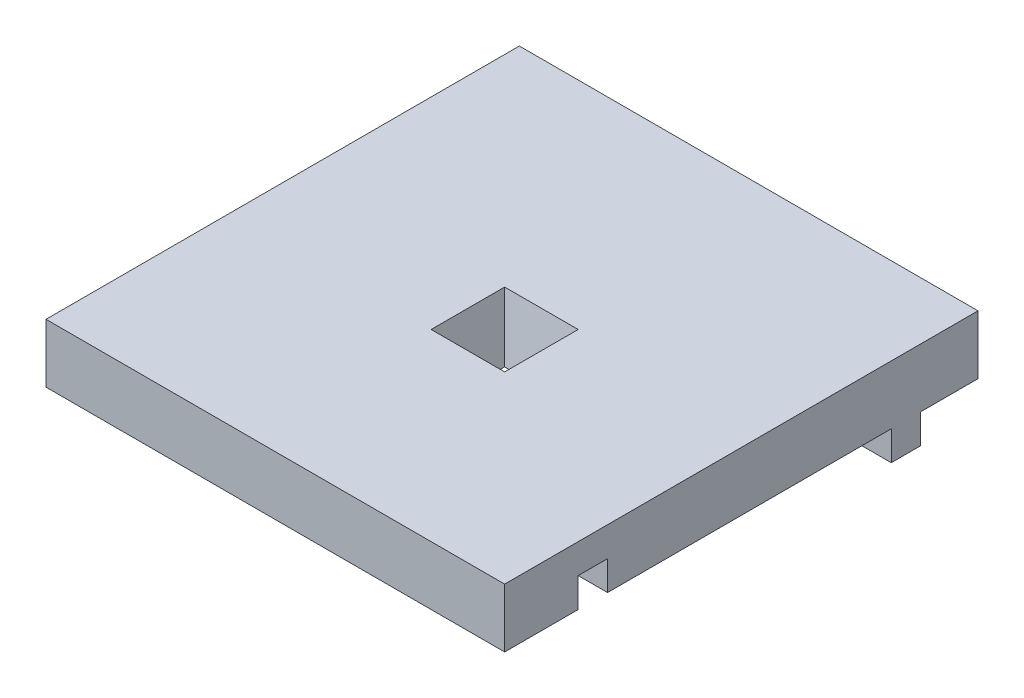
SolidWorks part; units mm, degrees
ref_plane "Front Plane" through (0, 0, 0) normal (0, 0, 1) x (1, 0, 0)
ref_plane "Top Plane" through (0, 0, 0) normal (0, 1, 0) x (1, 0, 0)
ref_plane "Right Plane" through (0, 0, 0) normal (1, 0, 0) x (0, 0, -1)
sketch "Sketch1" plane through (0, 0, 0) normal (0, 1, 0) x (1, 0, 0)
  line L1 (0, 0) -> (31.2, 0)
  line L2 (0, 0) -> (0, -32.2)
  line L3 (0, -32.2) -> (31.2, -32.2)
  line L4 (31.2, 0) -> (31.2, -32.2)
  dimension "D1" = 32.2
  dimension "D2" = 31.2
extrude "Body" add sketch "Sketch1" along normal blind 4
sketch "Sketch2" plane through (0, 0, 0) normal (0, -1, 0) x (-1, 0, 0)
  line L0 (-31.2, 0) -> (0, 0) construction
  line L1 (0, -5.9) -> (-2, -5.9)
  line L2 (0, -5.9) -> (0, -3.9)
  line L3 (0, -3.9) -> (-2, -3.9)
  line L4 (-2, -5.9) -> (-2, -3.9)
  line L5 (-29.2, -27.2) -> (-31.2, -27.2)
  line L6 (-29.2, -27.2) -> (-29.2, -25.2)
  line L7 (-29.2, -25.2) -> (-31.2, -25.2)
  line L8 (-31.2, -27.2) -> (-31.2, -25.2)
  line L10 (0, 0) -> (0, -32.2) construction
  line L11 (0, -32.2) -> (-31.2, -32.2) construction
  line L13 (-31.2, -32.2) -> (-31.2, 0) construction
  point P10 (-1, -3.9)
  dimension "D1" = 3.9
  dimension "D2" = 2
  dimension "D3" = 2
  dimension "D4" = 5
  dimension "D5" = 2
  dimension "D6" = 2
extrude "Female Tabs" cut sketch "Sketch2" against normal blind 2
sketch "Sketch3" plane through (0, 0, 0) normal (0, -1, 0) x (-1, 0, 0)
  line L0 (-31.2, -27.2) -> (-29.2, -27.2) construction
  line L1 (0, -27.2) -> (-2, -27.2)
  line L2 (0, -27.2) -> (0, -25.2)
  line L3 (0, -25.2) -> (-2, -25.2)
  line L4 (-2, -27.2) -> (-2, -25.2)
  line L5 (-29.2, -5.9) -> (-31.2, -5.9)
  line L6 (-29.2, -5.9) -> (-29.2, -3.9)
  line L7 (-29.2, -3.9) -> (-31.2, -3.9)
  line L8 (-31.2, -5.9) -> (-31.2, -3.9)
  line L9 (0, -5.9) -> (0, -32.2) construction
  line L10 (-31.2, -25.2) -> (-31.2, 0) construction
  line L11 (0, -3.9) -> (-2, -3.9) construction
  dimension "D1" = 2
  dimension "D2" = 2
  dimension "D3" = 2
  dimension "D4" = 2
extrude "Male Tabs" add sketch "Sketch3" along normal blind 2
sketch "Sketch4" plane through (0, 4, 0) normal (0, 1, 0) x (1, 0, 0)
  line L0 (0, -32.2) -> (31.2, -32.2) construction
  line L1 (18.7, -19.7) -> (13.7, -19.7)
  line L2 (18.7, -19.7) -> (18.7, -14.7)
  line L3 (18.7, -14.7) -> (13.7, -14.7)
  line L4 (13.7, -19.7) -> (13.7, -14.7)
  line L5 (31.2, 0) -> (0, 0) construction
  line L8 (31.2, -32.2) -> (31.2, 0) construction
  dimension "D1" = 5
  dimension "D2" = 5
  dimension "D3" = 12.5
  dimension "D4" = 12.5
extrude "Cut-Extrude2" cut sketch "Sketch4" against normal up to surface (4 mm away) draft 10
